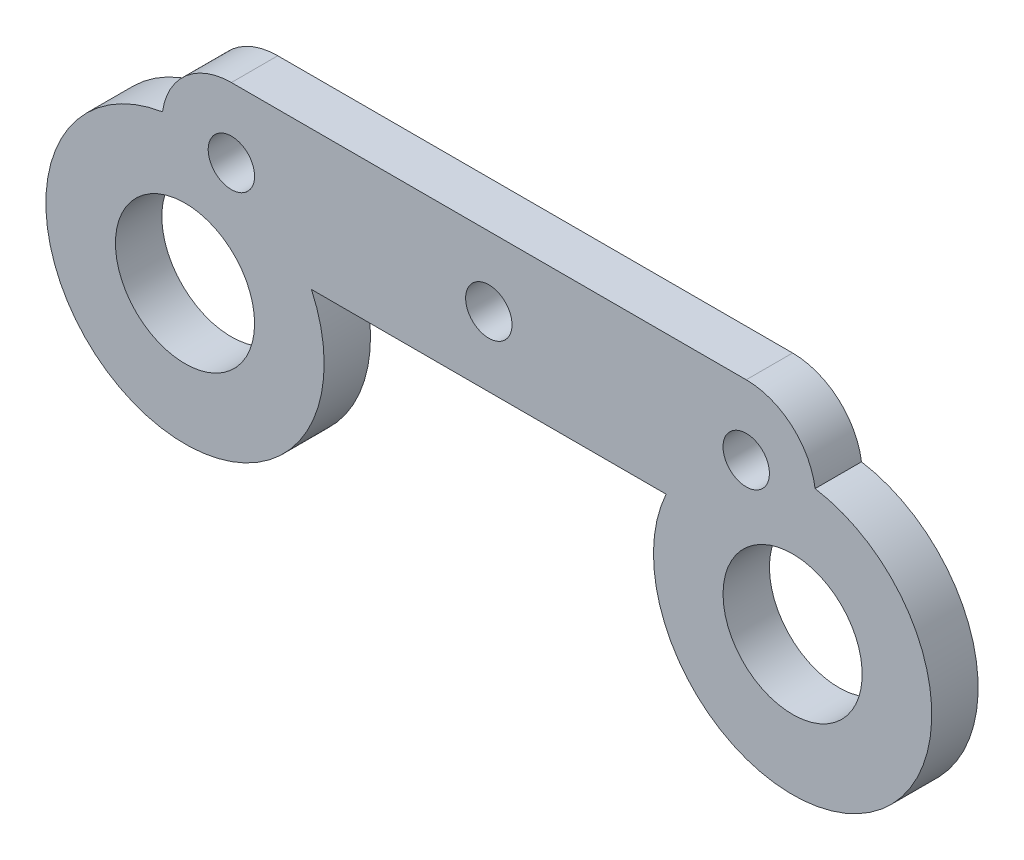
SolidWorks part; units mm, degrees
ref_plane "Front Plane" through (0, 0, 0) normal (0, 0, 1) x (1, 0, 0)
ref_plane "Top Plane" through (0, 0, 0) normal (0, 1, 0) x (1, 0, 0)
ref_plane "Right Plane" through (0, 0, 0) normal (1, 0, 0) x (0, 0, -1)
sketch "Sketch1" plane through (0, 0, 0) normal (0, 0, 1) x (1, 0, 0)
  line L2 (-11.1002, 3) -> (11.1002, 3)
  line L3 (-7.6458, -3) -> (7.6458, -3)
  circle A0 centre (0, 0) radius 1
  circle A4 centre (-13.1002, -5.5) radius 3
  circle A5 centre (13.1002, -5.5) radius 3
  arc A9 (14.0705, 0.421) -> (11.1002, 3) centre (11.1002, 0) ccw
  circle A13 centre (-11.1002, 0) radius 1
  arc A14 (-11.1002, 3) -> (-14.0705, 0.421) centre (-11.1002, 0) ccw
  circle A15 centre (11.1002, 0) radius 1
  arc A16 (-14.0705, 0.421) -> (-7.6458, -3) centre (-13.1002, -5.5) ccw
  arc A18 (7.6458, -3) -> (14.0705, 0.421) centre (13.1002, -5.5) ccw
  dimension "D3" = 6
  dimension "D4" = 2
  dimension "D5" = 2
  dimension "D6" = 2
  dimension "D8" = 6
  dimension "D9" = 6
  dimension "D10" = 11.1002
  dimension "D2" = 6
  dimension "D1" = 15.2917
  dimension "D7" = 22.2004
extrude "Boss-Extrude1" add sketch "Sketch1" along normal blind 2
sketch "Sketch2" plane through (0, -3, 0) normal (0, -1, 0) x (1, 0, 0)
  circle A0 centre (0, 1) radius 0.5
extrude "Cut-Extrude1" cut sketch "Sketch2" against normal blind 0.5
